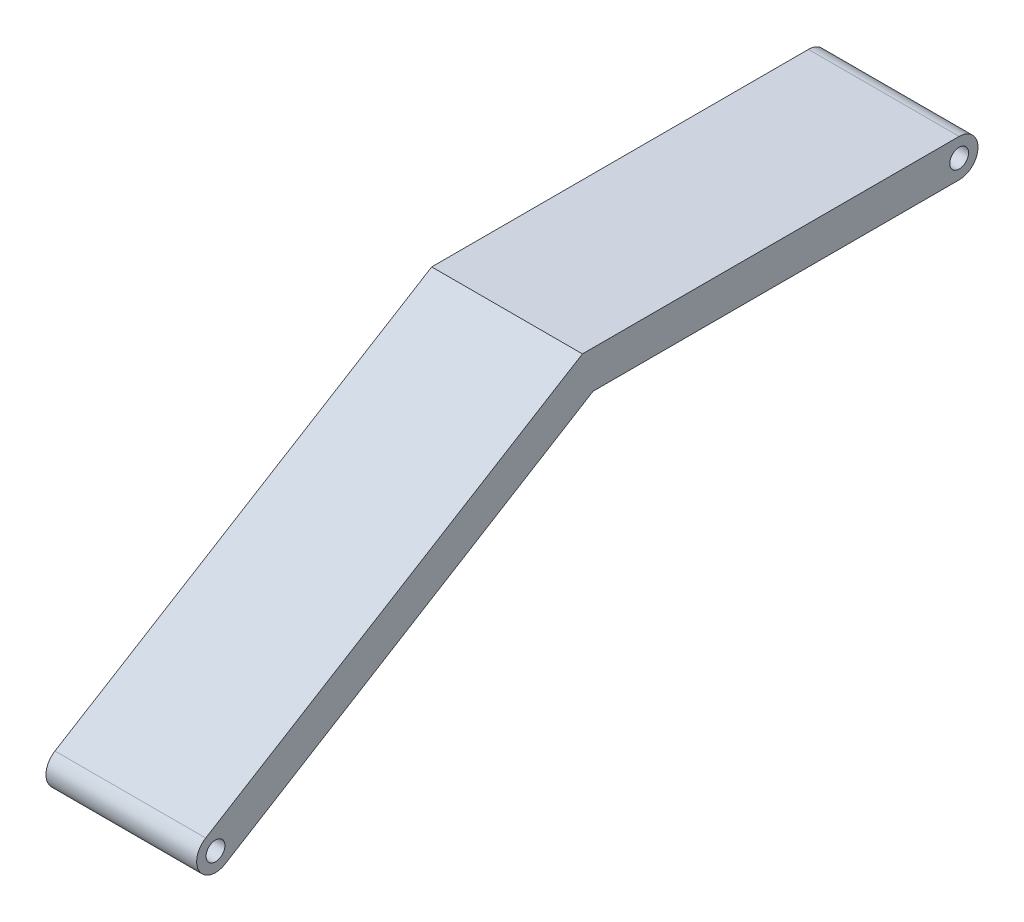
SolidWorks part; units mm, degrees
ref_plane "前视基准面" through (0, 0, 0) normal (0, 0, 1) x (1, 0, 0)
ref_plane "上视基准面" through (0, 0, 0) normal (0, 1, 0) x (1, 0, 0)
ref_plane "右视基准面" through (0, 0, 0) normal (1, 0, 0) x (0, 0, -1)
other "Configuration Table"
sketch "草图1" plane through (0, 0, 0) normal (1, 0, 0) x (0, 0, -1)
  line L0 (-4.326, 1.7686) -> (5.674, 1.7686)
  line L1 (5.674, 1.7686) -> (5.674, 0.7686)
  line L2 (5.674, 0.7686) -> (-4.044, 0.7686)
  line L3 (-4.044, 0.7686) -> (-13.8035, -5.2124)
  line L4 (-13.8035, -5.2124) -> (-14.326, -4.3598)
  line L5 (-14.326, -4.3598) -> (-4.326, 1.7686)
  point P8 (-12.014, 11.7401)
  point P9 (-15.2363, 0.5)
  dimension "D1" = 1
  dimension "D2" = 1
  dimension "D3" = 10
  dimension "D4" = 10
extrude "凸台-拉伸2" add sketch "草图1" along normal blind 4 contours L2 L3 L4 L5 L0 L1
sketch "草图2" plane through (4, 0, 0) normal (1, 0, 0) x (0, 0, -1)
  line L0 (5.674, 0.7686) -> (5.674, 1.7686)
  line L2 (-14.326, -4.3598) -> (-13.8035, -5.2124)
  arc A0 (5.674, 1.7686) -> (5.674, 0.7686) centre (5.674, 1.2686) cw
  arc A1 (-13.8035, -5.2124) -> (-14.326, -4.3598) centre (-14.0648, -4.7861) cw
extrude "凸台-拉伸3" add sketch "草图2" against normal blind 4
sketch "草图3" plane through (4, 0, 0) normal (1, 0, 0) x (0, 0, -1)
  circle A0 centre (-14.0648, -4.7861) radius 0.25
  circle A1 centre (5.674, 1.2686) radius 0.25
  dimension "D1" = 0.5
  dimension "D2" = 0.5
extrude "切除-拉伸1" cut sketch "草图3" against normal blind 4
